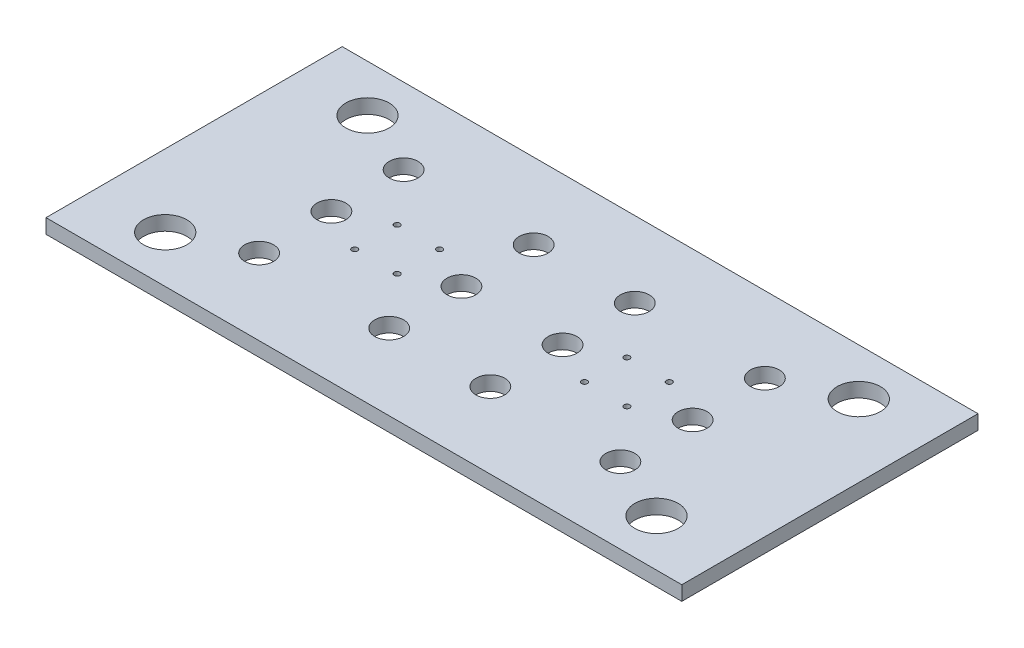
SolidWorks part; units mm, degrees
ref_plane "Front Plane" through (0, 0, 0) normal (0, 0, 1) x (1, 0, 0)
ref_plane "Top Plane" through (0, 0, 0) normal (0, 1, 0) x (1, 0, 0)
ref_plane "Right Plane" through (0, 0, 0) normal (1, 0, 0) x (0, 0, -1)
sketch "Sketch1" plane through (0, 0, 0) normal (0, 1, 0) x (1, 0, 0)
  line L1 (-440, 205) -> (440, 205)
  line L2 (-440, 205) -> (-440, -205)
  line L3 (-440, -205) -> (440, -205)
  line L4 (440, 205) -> (440, -205)
  line L5 (0, -205) -> (0, 205) construction
  line L6 (-440, 0) -> (440, 0) construction
  point P0 (0, 0)
extrude "Boss-Extrude1" add sketch "Sketch1" along normal blind 20
sketch "Sketch3" plane through (0, 20, 0) normal (0, 1, 0) x (1, 0, 0)
  circle A0 centre (-340, 140) radius 30
  circle A1 centre (340, 140) radius 30
  circle A2 centre (340, -140) radius 30
  circle A3 centre (-340, -140) radius 30
  dimension "D1" = 680
  dimension "D2" = 340
  dimension "D3" = 140
extrude "Cut-Extrude1" cut sketch "Sketch3" against normal blind 142
sketch "Sketch4" plane through (0, 20, 0) normal (0, 1, 0) x (1, 0, 0)
  circle A0 centre (-129.6551, 29.3449) radius 4
  circle A1 centre (-129.6551, -29.3449) radius 4
  circle A2 centre (-188.3449, -29.3449) radius 4
  circle A3 centre (-188.3449, 29.3449) radius 4
  circle A4 centre (188.3449, 29.3449) radius 4
  circle A5 centre (188.3449, -29.3449) radius 4
  circle A6 centre (129.6551, -29.3449) radius 4
  circle A7 centre (129.6551, 29.3449) radius 4
  point P0 (-159, 0)
  point P13 (-159, 0)
  point P21 (159, 0)
  dimension "D1" = 159
  dimension "D2" = 4
extrude "Cut-Extrude2" cut sketch "Sketch4" against normal blind 136
sketch "Sketch5" plane through (0, 0, 0) normal (0, -1, 0) x (1, 0, 0)
  circle A0 centre (-188.3449, 29.3449) radius 6
  circle A1 centre (-129.6551, 29.3449) radius 6
  circle A2 centre (-129.6551, -29.3449) radius 6
  circle A3 centre (-188.3449, -29.3449) radius 6
extrude "Cut-Extrude3" cut sketch "Sketch5" against normal blind 6
mirror "Mirror1" about plane through (0, 0, 0) normal (1, 0, 0) of "Cut-Extrude3"
sketch "Sketch7" plane through (0, 0, 0) normal (0, -1, 0) x (1, 0, 0)
  circle A0 centre (-250, 0) radius 20
  circle A1 centre (-250, 100) radius 20
  circle A2 centre (-250, -100) radius 20
  circle A3 centre (-70, 100) radius 20
  circle A4 centre (-70, 0) radius 20
  circle A5 centre (-70, -100) radius 20
  circle A6 centre (70, -100) radius 20
  circle A7 centre (70, 0) radius 20
  circle A8 centre (70, 100) radius 20
  circle A9 centre (250, -100) radius 20
  circle A10 centre (250, 100) radius 20
  circle A11 centre (250, 0) radius 20
  dimension "D1" = 250
  dimension "D2" = 100
  dimension "D3" = 100
  dimension "D4" = 70
  dimension "D5" = 70
  dimension "D6" = 0
extrude "Cut-Extrude4" cut sketch "Sketch7" against normal blind 261
